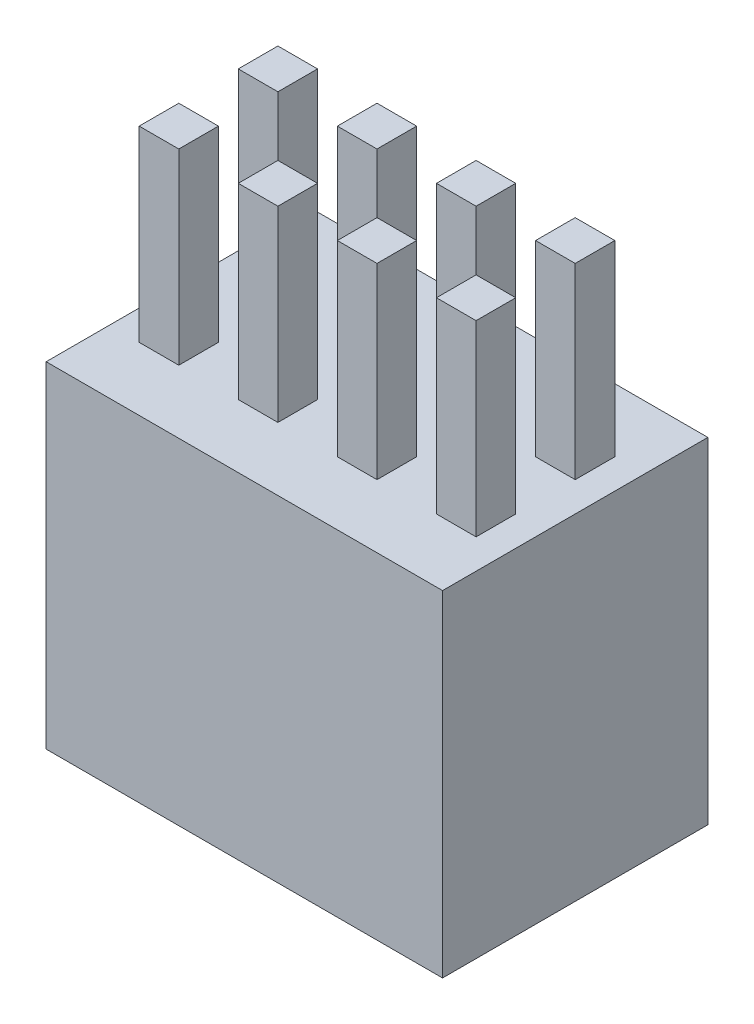
SolidWorks part; units mm, degrees
ref_plane "Front Plane" through (0, 0, 0) normal (0, 0, 1) x (1, 0, 0)
ref_plane "Top Plane" through (0, 0, 0) normal (0, 1, 0) x (1, 0, 0)
ref_plane "Right Plane" through (0, 0, 0) normal (1, 0, 0) x (0, 0, -1)
sketch "Sketch1" plane through (0, 0, 0) normal (0, 1, 0) x (1, 0, 0)
  line L1 (-2.54, -1.7) -> (2.54, -1.7)
  line L2 (-2.54, -1.7) -> (-2.54, 1.7)
  line L3 (-2.54, 1.7) -> (2.54, 1.7)
  line L4 (2.54, -1.7) -> (2.54, 1.7)
  line L5 (-2.54, -1.7) -> (2.54, 1.7) construction
  line L6 (-2.54, 1.7) -> (2.54, -1.7) construction
  point P0 (0, 0)
  dimension "D1" = 5.08
  dimension "D2" = 3.4
extrude "Boss-Extrude1" add sketch "Sketch1" along normal mid plane 4.3
sketch "Sketch2" plane through (0, 0, 0) normal (0, 1, 0) x (1, 0, 0)
  line L0 (-0.889, -0.381) -> (-0.381, -0.381)
  line L1 (-2.159, -0.381) -> (-1.651, -0.381)
  line L2 (-2.159, -0.381) -> (-2.159, -0.889)
  line L3 (-2.159, -0.889) -> (-1.651, -0.889)
  line L4 (-1.651, -0.381) -> (-1.651, -0.889)
  line L5 (-2.159, -0.381) -> (-1.651, -0.889) construction
  line L6 (-2.159, -0.889) -> (-1.651, -0.381) construction
  line L7 (-0.889, -0.381) -> (-0.889, -0.889)
  line L8 (-0.889, -0.889) -> (-0.381, -0.889)
  line L9 (-0.381, -0.381) -> (-0.381, -0.889)
  line L10 (-0.889, -0.381) -> (-0.381, -0.889) construction
  line L11 (-0.889, -0.889) -> (-0.381, -0.381) construction
  line L12 (0.381, -0.381) -> (0.889, -0.381)
  line L13 (0.381, -0.381) -> (0.381, -0.889)
  line L14 (0.381, -0.889) -> (0.889, -0.889)
  line L15 (0.889, -0.381) -> (0.889, -0.889)
  line L16 (0.381, -0.381) -> (0.889, -0.889) construction
  line L17 (0.381, -0.889) -> (0.889, -0.381) construction
  line L18 (1.651, -0.381) -> (2.159, -0.381)
  line L19 (1.651, -0.381) -> (1.651, -0.889)
  line L20 (1.651, -0.889) -> (2.159, -0.889)
  line L21 (2.159, -0.381) -> (2.159, -0.889)
  line L22 (1.651, -0.381) -> (2.159, -0.889) construction
  line L23 (1.651, -0.889) -> (2.159, -0.381) construction
  line L24 (-0.889, 0.889) -> (-0.381, 0.889)
  line L25 (-0.889, 0.889) -> (-0.889, 0.381)
  line L26 (-0.889, 0.381) -> (-0.381, 0.381)
  line L27 (-0.381, 0.889) -> (-0.381, 0.381)
  line L28 (-0.889, 0.889) -> (-0.381, 0.381) construction
  line L29 (-0.889, 0.381) -> (-0.381, 0.889) construction
  line L30 (0.381, 0.889) -> (0.889, 0.889)
  line L31 (0.381, 0.889) -> (0.381, 0.381)
  line L32 (0.381, 0.381) -> (0.889, 0.381)
  line L33 (0.889, 0.889) -> (0.889, 0.381)
  line L34 (0.381, 0.889) -> (0.889, 0.381) construction
  line L35 (0.381, 0.381) -> (0.889, 0.889) construction
  line L36 (1.651, 0.889) -> (2.159, 0.889)
  line L37 (1.651, 0.889) -> (1.651, 0.381)
  line L38 (1.651, 0.381) -> (2.159, 0.381)
  line L39 (2.159, 0.889) -> (2.159, 0.381)
  line L40 (1.651, 0.889) -> (2.159, 0.381) construction
  line L41 (1.651, 0.381) -> (2.159, 0.889) construction
  line L42 (-2.159, 0.889) -> (-1.651, 0.889)
  line L43 (-2.159, 0.889) -> (-2.159, 0.381)
  line L44 (-2.159, 0.381) -> (-1.651, 0.381)
  line L45 (-1.651, 0.889) -> (-1.651, 0.381)
  line L46 (-2.159, 0.889) -> (-1.651, 0.381) construction
  line L47 (-2.159, 0.381) -> (-1.651, 0.889) construction
  line L48 (-1.905, 0.635) -> (-1.905, -0.635) construction
  line L49 (-1.905, 0.635) -> (1.905, 0.635) construction
  point P0 (-1.905, -0.635)
  point P5 (-1.905, 0)
  point P7 (-0.635, -0.635)
  point P12 (0.635, -0.635)
  point P17 (1.905, -0.635)
  point P22 (-0.635, 0.635)
  point P27 (0.635, 0.635)
  point P32 (1.905, 0.635)
  point P37 (-1.905, 0.635)
  point P43 (0, 0.635)
  dimension "D3" = 3.81
  dimension "D4" = 1.27
  dimension "D5" = 0.508
  dimension "D1" = 4
  dimension "D2" = 2
extrude "Boss-Extrude2" add sketch "Sketch2" along normal offset from surface (4.55 mm away) 2.4 up to face at (0, 2.15, 0) offset beyond the face yes
ref_plane "Plane1" through (0, 0, -0.635) normal (0, 0, 1) x (1, 0, 0)
